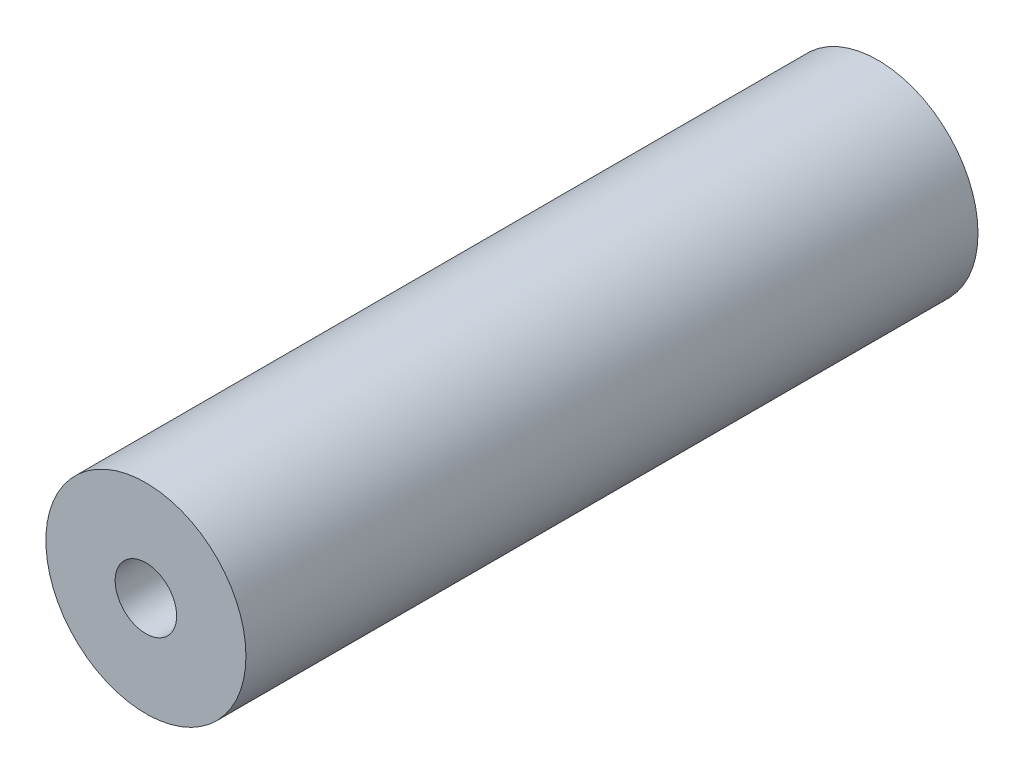
SolidWorks part; units mm, degrees
ref_plane "Alzado" through (0, 0, 0) normal (0, 0, 1) x (1, 0, 0)
ref_plane "Planta" through (0, 0, 0) normal (0, 1, 0) x (1, 0, 0)
ref_plane "Vista lateral" through (0, 0, 0) normal (1, 0, 0) x (0, 0, -1)
sketch "Croquis1" plane through (0, 0, 0) normal (0, 0, 1) x (1, 0, 0)
  circle A0 centre (0, 0) radius 0.63
  circle A1 centre (0, 0) radius 2.05
  dimension "D1" = 4.1
  dimension "D2" = 1.26
extrude "Saliente-Extruir1" add sketch "Croquis1" along normal blind 15
equation "\"k\"= 52.6246"
equation "\"A_ALETA\"= ( ( ( tan ( \"ANG_ALETA\" ) ) * \"L_ALETA\" ) + \"A_BASE\" - ( \"GAP_ALETAS\" / 2 ) )"
equation "\"A_BASE\"= ( \"L_DIE\" - \"E_CAJA\" )"
equation "\"L_ALETA\"=90.000000"
equation "\"TAU_ALETA\"= ( \"L_ALETA\" / ( log ( ( \"A_ALETA\" ) + 1 ) ) )"
equation "\"E_ALETA\"=5.000000"
equation "\"R_SONDA\"= 2.05"
equation "\"D_SONDA\"=20.000000"
equation "\"L_CAJA\"=25.000000"
equation "\"E_CAJA\"= 2.5"
equation "\"A_CAJA\"= ( 2 * \"A_BASE\" ) + \"GAP_ALETAS\""
equation "\"W_CAJA\"= \"A_CAJA\" * \"CONST_CAJA\""
equation "\"W_CONC\"= ( \"W_CAJA\" / \"CONST_CONC\" ) "
equation "\"A_CONC\"= ( \"A_CAJA\" / \"CONST_CONC\" )"
equation "\"L_CONC\"= \"D_SONDA\" - \"OFFSET_CONC\""
equation "\"W_ALETA\"=70.000000"
equation "\"L_DIE_SONDA\"= ( \"GAP_ALETAS\" / 4 )"
equation "\"GAP_ALETAS\"=1.500000"
equation "\"D1@Saliente-Extruir1\" = \"L_DIE\""
equation "\"CONST_CONC\"=2.000000"
equation "\"K\"= 1.5"
equation "\"L_DIE\"= 15"
equation "\"L_CI\"= 18"
equation "\"CONST_CAJA\"=2.000000"
equation "\"ANG_ALETA\"=15.000000"
equation "\"R_C_SONDA\"= 0.63"
equation "\"D2@Croquis1\"=\"R_C_SONDA\"*2"
equation "\"D1@Croquis1\"=\"R_SONDA\"*2"
equation "\"TOLERANCIA\"= 0.1"
equation "\"OFFSET_CONC\"= ( 2 * \"R_TORNILLO\" )"
equation "\"R_TORNILLO\"=2.600000"
